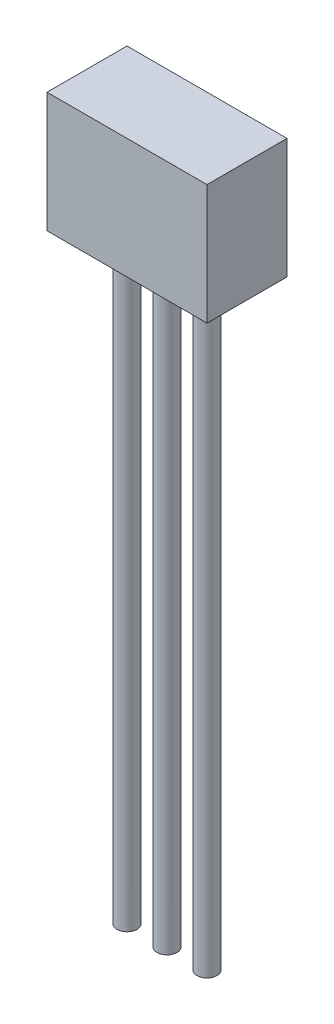
SolidWorks part; units mm, degrees
ref_plane "Front Plane" through (0, 0, 0) normal (0, 0, 1) x (1, 0, 0)
ref_plane "Top Plane" through (0, 0, 0) normal (0, 1, 0) x (1, 0, 0)
ref_plane "Right Plane" through (0, 0, 0) normal (1, 0, 0) x (0, 0, -1)
sketch "Sketch2" plane through (0, 0, 0) normal (0, 1, 0) x (1, 0, 0)
  line L2 (-2, 0) -> (-2, 1)
  line L3 (2, 0) -> (2, 1)
  line L4 (2, 1) -> (-2, 1)
  line L5 (-2, 0) -> (-2, -1)
  line L6 (2, 0) -> (2, -1)
  line L7 (2, -1) -> (-2, -1)
extrude "Head" add sketch "Sketch2" along normal blind 3
sketch "Sketch3" plane through (0, 0, 0) normal (0, 1, 0) x (1, 0, 0)
  circle A0 centre (0, 0) radius 0.25
  circle A1 centre (-1, 0) radius 0.25
  circle A2 centre (1, 0) radius 0.25
  point P9 (0, 0)
extrude "Pins" add sketch "Sketch3" against normal blind 15 contours A1 | A2 | A0
